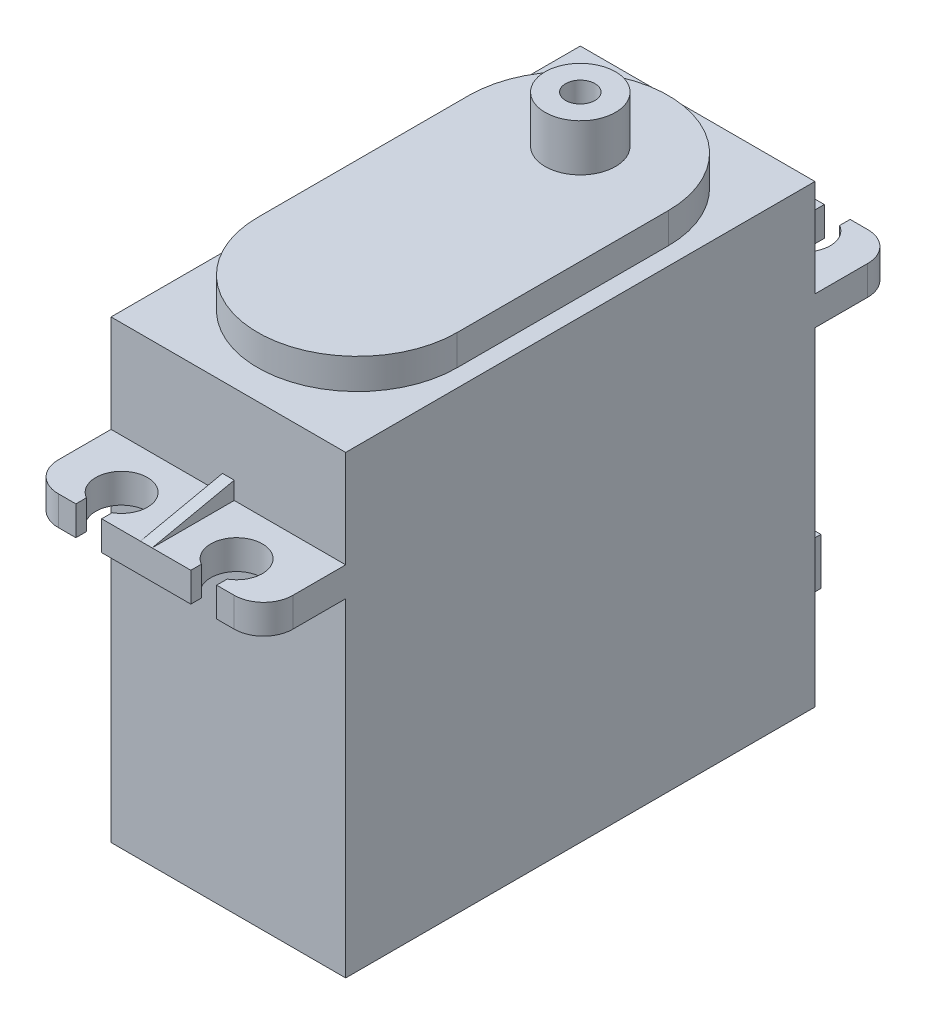
SolidWorks part; units mm, degrees
ref_plane "前视基准面" through (0, 0, 0) normal (0, 0, 1) x (1, 0, 0)
ref_plane "上视基准面" through (0, 0, 0) normal (0, 1, 0) x (1, 0, 0)
ref_plane "右视基准面" through (0, 0, 0) normal (1, 0, 0) x (0, 0, -1)
other "Configuration Table"
sketch "草图1" plane through (0, 0, 0) normal (0, 1, 0) x (1, 0, 0)
  line L1 (-10, 20) -> (10, 20)
  line L2 (-10, 20) -> (-10, -20)
  line L3 (-10, -20) -> (10, -20)
  line L4 (10, 20) -> (10, -20)
  line L5 (-10, 20) -> (10, -20) construction
  line L6 (-10, -20) -> (10, 20) construction
  point P0 (0, 0)
  dimension "D1" = 40
  dimension "D2" = 20
extrude "凸台-拉伸1" add sketch "草图1" along normal blind 38.8
sketch "草图2" plane through (0, 0, 0) normal (0, 1, 0) x (1, 0, 0)
  line L0 (-10, 20) -> (-10, -20) construction
  line L1 (-7.5, -27) -> (-6, -27)
  line L2 (-10, -24.5) -> (-10, 24.5)
  line L3 (-7.5, 27) -> (-6, 27)
  line L4 (10, -24.5) -> (10, 24.5)
  line L5 (-10, -27) -> (10, 27) construction
  line L6 (-10, 27) -> (10, -27) construction
  line L7 (0, 42.6693) -> (0, -40.1574) construction
  line L8 (-24.1871, 0) -> (28.7742, 0) construction
  line L9 (-4.9, 28.4699) -> (-4.9, 24.2) construction
  line L10 (-6, 27) -> (-6, 26.1053)
  line L11 (-3.8, 27) -> (-3.8, 26.1053)
  line L12 (-3.8, 27) -> (3.8, 27)
  line L13 (3.8, 27) -> (3.8, 26.1053)
  line L14 (6, 27) -> (6, 26.1053)
  line L15 (6, 27) -> (7.5, 27)
  line L16 (6, -27) -> (6, -26.1053)
  line L17 (3.8, -27) -> (3.8, -26.1053)
  line L18 (-3.8, -27) -> (-3.8, -26.1053)
  line L19 (-6, -27) -> (-6, -26.1053)
  line L20 (-3.8, -27) -> (3.8, -27)
  line L21 (6, -27) -> (7.5, -27)
  arc A0 (-6, 26.1053) -> (-3.8, 26.1053) centre (-4.9, 24.2) ccw
  arc A4 (6, 26.1053) -> (3.8, 26.1053) centre (4.9, 24.2) cw
  arc A5 (6, -26.1053) -> (3.8, -26.1053) centre (4.9, -24.2) ccw
  arc A6 (-6, -26.1053) -> (-3.8, -26.1053) centre (-4.9, -24.2) cw
  arc A7 (-10, 24.5) -> (-7.5, 27) centre (-7.5, 24.5) cw
  arc A8 (10, 24.5) -> (7.5, 27) centre (7.5, 24.5) ccw
  arc A9 (7.5, -27) -> (10, -24.5) centre (7.5, -24.5) ccw
  arc A10 (-10, -24.5) -> (-7.5, -27) centre (-7.5, -24.5) ccw
  point P0 (0, 0)
  dimension "D2" = 4.4
  dimension "D6" = 2.5
  dimension "D1" = 54
  dimension "D3" = 2.2
  dimension "D4" = 9.8
  dimension "D5" = 48.4
extrude "凸台-拉伸2" add sketch "草图2" along normal blind 2.5 from offset 28
sketch "草图3" plane through (0, 0, 0) normal (1, 0, 0) x (0, 0, -1)
  line L0 (0, 55.7992) -> (0, 0) construction
  line L1 (-20, 30.5) -> (-27, 30.5)
  line L2 (-27, 30.5) -> (-20, 32)
  line L3 (20, 32) -> (20, 30.5)
  line L4 (-20, 32) -> (-20, 30.5)
  line L8 (-24.5, 30.5) -> (-20, 30.5) construction
  line L9 (27, 30.5) -> (20, 32)
  line L10 (20, 30.5) -> (27, 30.5)
  point P6 (0, 0)
  point P9 (0, 0)
  point P10 (-26.5255, 30.1088)
  point P12 (-46.4504, 31.4739)
  point P13 (0, 0)
  dimension "D1" = 1.5
extrude "凸台-拉伸3" add sketch "草图3" along normal mid plane 1
sketch "草图4" plane through (0, 0, 0) normal (0, 1, 0) x (1, 0, 0)
  line L0 (-19.4568, 0) -> (19.4568, 0) construction
  line L2 (8.5, -9) -> (8.5, 9)
  line L4 (-8.5, -9) -> (-8.5, 9)
  line L5 (0, 0) -> (0, 33.0045) construction
  arc A0 (8.5, 9) -> (-8.5, 9) centre (0, 9) ccw
  arc A1 (8.5, -9) -> (-8.5, -9) centre (0, -9) cw
  point P0 (0, 0)
  point P12 (8.5, 0)
  point P13 (-8.5, 0)
  point P14 (0, 17.5)
  point P15 (0, -17.5)
  dimension "D2" = 35
  dimension "D1" = 17
  dimension "D3" = 18
  dimension "D4" = 18
extrude "凸台-拉伸4" add sketch "草图4" along normal blind 2.6 from surface at 38.8 starting at face at (0, 38.8, 0)
sketch "草图5" plane through (0, 0, 0) normal (0, 1, 0) x (1, 0, 0)
  line L0 (0, 30.7966) -> (0, 0) construction
  circle A0 centre (0, 10) radius 3
  circle A1 centre (0, 10) radius 1.25
  dimension "D2" = 6
  dimension "D3" = 2.5
  dimension "D1" = 10
extrude "凸台-拉伸5" add sketch "草图5" along normal blind 4 from surface at 41.4 separate body starting at face at (0, 41.4, 0)
sketch "草图6" plane through (0, 0, 0) normal (0, 0, 1) x (1, 0, 0)
  line L0 (0, 18.3818) -> (0, 0) construction
  line L1 (-10, 0) -> (10, 0) construction
  line L2 (-3.5, 6) -> (3.5, 6)
  line L3 (-3.5, 6) -> (-3.5, 2)
  line L4 (-3.5, 2) -> (3.5, 2)
  line L5 (3.5, 6) -> (3.5, 2)
  line L6 (-3.5, 6) -> (3.5, 2) construction
  line L7 (-3.5, 2) -> (3.5, 6) construction
  point P3 (0, 4)
  dimension "D1" = 2
  dimension "D2" = 4
  dimension "D3" = 7
extrude "凸台-拉伸6" add sketch "草图6" against normal blind 7 from surface at -20 separate body starting at face at (0, 32.95, -20)
